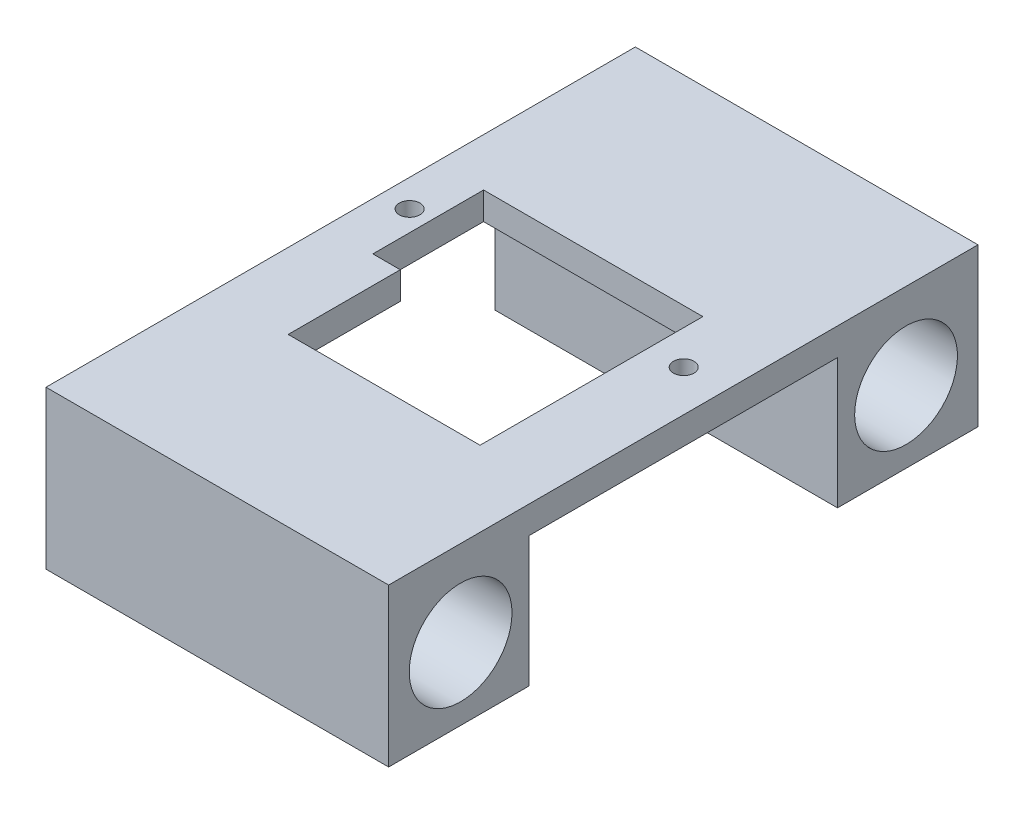
SolidWorks part; units mm, degrees
ref_plane "Front Plane" through (0, 0, 0) normal (0, 0, 1) x (1, 0, 0)
ref_plane "Top Plane" through (0, 0, 0) normal (0, 1, 0) x (1, 0, 0)
ref_plane "Right Plane" through (0, 0, 0) normal (1, 0, 0) x (0, 0, -1)
sketch "Sketch1" plane through (0, 0, 0) normal (1, 0, 0) x (0, 0, -1)
  line L0 (32.5, 0) -> (-32.5, 0) construction
  line L1 (0, 0) -> (0, 13.0358) construction
  line L2 (-32.5, -10.5) -> (-43, -10.5)
  line L6 (43, 12.5) -> (-43, 12.5)
  line L8 (43, -10.5) -> (-32.5, -10.5)
  line L9 (-43, 12.5) -> (-43, -10.5)
  line L10 (43, -10.5) -> (43, 12.5)
  circle A0 centre (-32.5, 0) radius 7.5
  circle A2 centre (32.5, 0) radius 7.5
  point P4 (0, 0)
  point P9 (-43, 0)
  point P10 (-32.5, -10.5)
  dimension "D2" = 15
  dimension "D1" = 65
  dimension "D3" = 10.5
  dimension "D4" = 10.5
  dimension "D5" = 23
extrude "Boss-Extrude1" add sketch "Sketch1" against normal mid plane 50
sketch "Sketch2" plane through (0, -10.5, 0) normal (0, -1, 0) x (1, 0, 0)
  line L0 (14, -13.8508) -> (-18, -13.8508)
  line L1 (14, 3.4414) -> (14, -15.5586) construction
  line L2 (-18, -15.5586) -> (-18, 3.4414) construction
  line L5 (14, -13.8508) -> (14, 18.6607)
  line L8 (14, 43.4414) -> (14, 3.4414) construction
  line L9 (-14, 18.6607) -> (14, 18.6607)
  line L10 (-18, -13.8508) -> (-18, 2.3043)
  line L11 (-18, 2.3043) -> (-14, 2.3043)
  line L12 (-14, -7.4406) -> (-14, 3.4414) construction
  line L13 (-14, 2.3043) -> (-14, 18.6607)
  line L14 (-14, 3.4414) -> (-14, 43.4414) construction
extrude "Cut-Extrude1" cut sketch "Sketch2" against normal blind 34
sketch "Sketch3" plane through (-25, 0, 0) normal (-1, 0, 0) x (0, 0, 1)
  line L6 (-22.5, -10.5) -> (-22.5, 8.5)
  line L7 (43, -10.5) -> (-43, -10.5) construction
  line L8 (-22.5, 8.5) -> (22.5, 8.5)
  line L9 (22.5, 8.5) -> (22.5, -10.5)
  line L10 (22.5, -10.5) -> (-22.5, -10.5)
  line L11 (-43, 12.5) -> (43, 12.5) construction
  circle A2 centre (-32.5, 0) radius 7.5 construction
  circle A3 centre (32.5, 0) radius 7.5 construction
  point P0 (-22.5, 0)
  point P4 (22.5, 0)
  dimension "D2" = 10
  dimension "D1" = 10
  dimension "D3" = 4
extrude "Cut-Extrude2" cut sketch "Sketch3" against normal blind 62
sketch "Sketch4" plane through (0, 8.5, 0) normal (0, -1, 0) x (1, 0, 0)
  circle A0 centre (-21, -6.0586) radius 1.5
  circle A1 centre (19, -6.0586) radius 1.5
extrude "Cut-Extrude3" cut sketch "Sketch4" against normal blind 62
